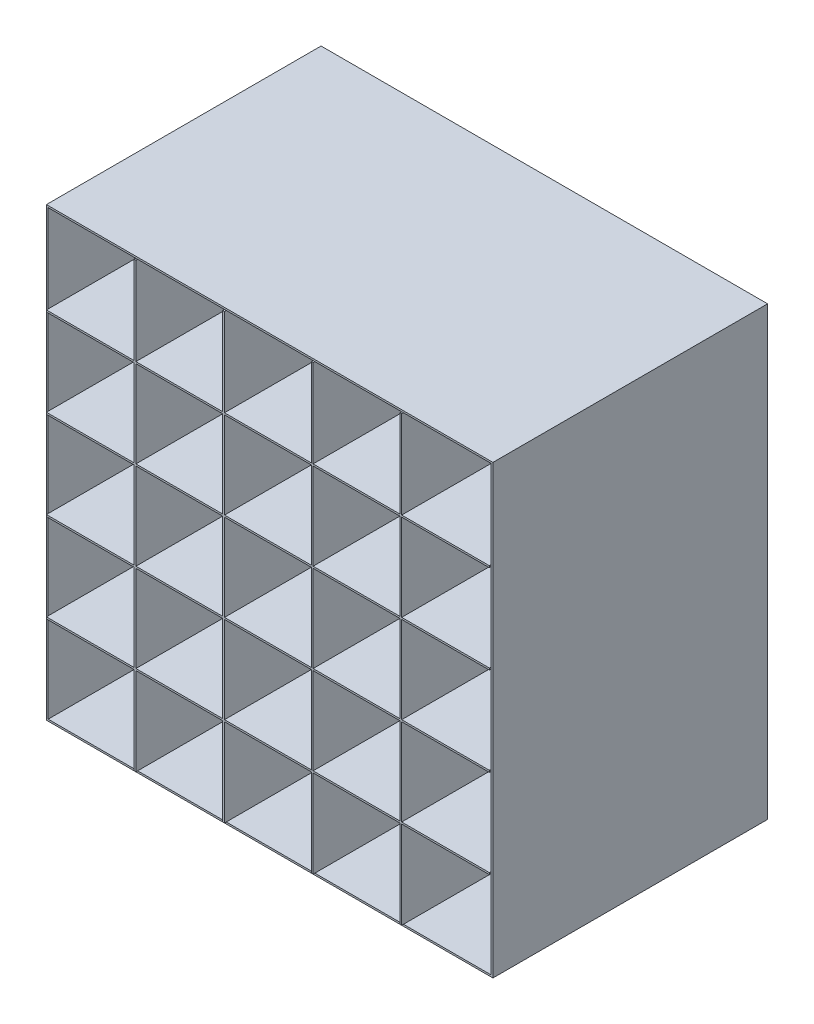
SolidWorks part; units mm, degrees
ref_plane "Alzado" through (0, 0, 0) normal (0, 0, 1) x (1, 0, 0)
ref_plane "Planta" through (0, 0, 0) normal (0, 1, 0) x (1, 0, 0)
ref_plane "Vista lateral" through (0, 0, 0) normal (1, 0, 0) x (0, 0, -1)
sketch "Sketch1" plane through (0, 0, 0) normal (0, 0, 1) x (1, 0, 0)
  line L0 (0, 0) -> (125, 0) construction
  line L1 (125, 0) -> (125, 125) construction
  line L2 (125, 125) -> (-125, 125)
  line L3 (-125, 125) -> (-125, -125)
  line L4 (-125, -125) -> (125, -125)
  line L5 (125, -125) -> (125, 125)
  line L6 (-125, 125) -> (-125, 126) construction
  line L7 (-125, 126) -> (-126, 126)
  line L8 (-126, 126) -> (-126, -126)
  line L9 (-126, -126) -> (126, -126)
  line L10 (-126, 126) -> (126, 126)
  line L11 (126, 126) -> (126, -126)
  dimension "D1" = 125
  dimension "D2" = 125
  dimension "D3" = 250
  dimension "D4" = 250
  dimension "D5" = 1
  dimension "D6" = 1
  dimension "D7" = 252
  dimension "D8" = 252
extrude "Boss-Extrude1" add sketch "Sketch1" along normal blind 50 contours L4 L5 L2 L3 | L10 L11 L9 L8
sketch "Sketch2" plane through (0, 0, 0) normal (0, 0, -1) x (-1, 0, 0)
  line L0 (-126, 126) -> (126, 126)
  line L1 (126, 126) -> (126, -126)
  line L2 (126, -126) -> (-126, -126)
  line L3 (-126, 126) -> (-126, -126) construction
  line L4 (126, -126) -> (-126, -126) construction
  line L5 (-126, -126) -> (-126, 126)
extrude "Boss-Extrude2" add sketch "Sketch2" along normal blind 5 and the other way blind 1
sketch "Sketch3" plane through (0, 0, 1) normal (0, 0, 1) x (1, 0, 0)
  line L0 (-125, 125) -> (-75, 125) construction
  line L1 (125, 125) -> (-125, 125) construction
  line L2 (-75, 125) -> (-25, 125) construction
  line L3 (125, 125) -> (-125, 125) construction
  line L4 (-25, 125) -> (25, 125) construction
  line L5 (25, 125) -> (75, 125) construction
  line L6 (-125, 125) -> (-125, 75) construction
  line L7 (-125, 125) -> (-125, -125) construction
  line L8 (-125, 75) -> (-125, 25) construction
  line L9 (-125, 125) -> (-125, -125) construction
  line L10 (-125, 25) -> (-125, -25) construction
  line L11 (-125, -25) -> (-125, -75) construction
  line L12 (-125, 75) -> (-125, 75.5) construction
  line L13 (-125, 75.5) -> (125, 75.5)
  line L14 (-125, 75.5) -> (-125, 74.5072)
  line L15 (-125, 74.5072) -> (125, 74.5072)
  line L16 (125, 74.5072) -> (125, 75.5)
  line L17 (-125, 25) -> (-125, 25.5)
  line L18 (-125, 25.5) -> (125, 25.5)
  line L19 (125, -125) -> (125, 125) construction
  line L20 (125, 25.5) -> (125, 24.5)
  line L21 (125, 24.5) -> (-125, 24.5)
  line L22 (-125, 24.5) -> (-125, 25.5)
  line L23 (-125, -25) -> (-125, -24.5)
  line L24 (-125, -24.5) -> (125, -24.5)
  line L25 (125, -125) -> (125, 125) construction
  line L26 (125, -24.5) -> (125, -25.5)
  line L27 (125, -25.5) -> (-125, -25.5)
  line L28 (-125, -25.5) -> (-125, -24.5)
  line L29 (-125, -75) -> (-125, -74.5)
  line L30 (-125, -74.5) -> (125, -74.5)
  line L31 (125, -74.5) -> (125, -75.5)
  line L32 (125, -75.5) -> (-125, -75.5)
  line L33 (-125, -75.5) -> (-125, -74.5)
  line L34 (-75, 125) -> (-74.5, 125)
  line L35 (-74.5, 125) -> (-74.5, -125)
  line L36 (-125, -125) -> (125, -125) construction
  line L37 (-74.5, -125) -> (-75.5, -125)
  line L38 (-75.5, -125) -> (-75.5, 125)
  line L39 (-75.5, 125) -> (-74.5, 125)
  line L40 (-25, 125) -> (-24.5, 125)
  line L41 (-24.5, 125) -> (-24.5, -125)
  line L42 (-24.5, -125) -> (-25.5, -125)
  line L43 (-125, -125) -> (125, -125) construction
  line L44 (-25.5, -125) -> (-25.5, 125)
  line L45 (-25.5, 125) -> (-24.5, 125)
  line L46 (25, 125) -> (25.5, 125)
  line L47 (25.5, 125) -> (25.5, -125)
  line L48 (25.5, -125) -> (24.5, -125)
  line L49 (24.5, -125) -> (24.5, 125)
  line L50 (24.5, 125) -> (25.5, 125)
  line L51 (75, 125) -> (75.5, 125)
  line L52 (75.5, 125) -> (75.5, -125)
  line L53 (75.5, -125) -> (74.5, -125)
  line L54 (74.5, -125) -> (74.5, 125)
  line L55 (74.5, 125) -> (75.5, 125)
  dimension "D1" = 50
  dimension "D2" = 50
  dimension "D3" = 50
  dimension "D4" = 50
  dimension "D5" = 50
  dimension "D6" = 50
  dimension "D7" = 50
  dimension "D8" = 50
  dimension "D9" = 49.5
  dimension "D10" = 1
  dimension "D11" = 0.5
  dimension "D12" = 0.5
  dimension "D13" = 1
  dimension "D14" = 0.5
  dimension "D15" = 1
  dimension "D16" = 0.5
  dimension "D17" = 1
  dimension "D18" = 0.5
  dimension "D19" = 1
  dimension "D20" = 0.5
  dimension "D21" = 1
  dimension "D22" = 0.5
  dimension "D23" = 1
extrude "Boss-Extrude3" add sketch "Sketch3" along normal blind 50 contours L30 L31 L32 L33 | L24 L26 L27 L28 | L18 L20 L21 L22 | L15 L16 L13 L14 | L52 L53 L54 L55 | L47 L48 L49 L50 | L41 L42 L44 L45 | L35 L37 L38 L39
sketch "Sketch4" plane through (0, 0, 1) normal (0, 0, 1) x (1, 0, 0)
  line L0 (0, 0) -> (0, 98.6886) construction
  line L1 (0, 98.6886) -> (50, 98.6886) construction
  line L2 (50, 98.6886) -> (100, 98.6886) construction
  line L3 (100, 98.6886) -> (100, 48.6886) construction
  line L4 (100, 48.6886) -> (100, -1.3114) construction
  line L5 (100, -1.3114) -> (100, -51.3114) construction
  line L6 (100, -51.3114) -> (100, -101.3114) construction
  line L7 (100, -101.3114) -> (46.1074, -101.3114) construction
  line L8 (46.1074, -101.3114) -> (0, -101.3114) construction
  line L9 (0, -101.3114) -> (-50, -101.3114) construction
  line L10 (-50, -101.3114) -> (-100, -101.3114) construction
  line L11 (-100, -101.3114) -> (-100, -45.3639) construction
  line L12 (-100, -45.3639) -> (-100, 5.4624) construction
  line L13 (-100, 5.4624) -> (-100, 54.8067) construction
  line L14 (-100, 54.8067) -> (-100, 98.6886) construction
  line L15 (-100, 98.6886) -> (-50, 98.6886) construction
  line L16 (-50, 98.6886) -> (-50, 49.3443) construction
  line L17 (-50, 49.3443) -> (-50, 0) construction
  line L18 (-50, 0) -> (-50, -50.8263) construction
  line L19 (-50, -50.8263) -> (-1.5755, -50.8263) construction
  line L20 (-1.5755, -50.8263) -> (50, -50.8263) construction
  line L21 (50, -50.8263) -> (50, 0) construction
  line L22 (50, 0) -> (50, 49.3443) construction
  line L23 (50, 49.3443) -> (0, 49.3443) construction
  circle A0 centre (-100, 98.6886) radius 2.5
  circle A1 centre (-50, 98.6886) radius 2.5
  circle A2 centre (0, 98.6886) radius 2.5
  circle A3 centre (50, 98.6886) radius 2.5
  circle A4 centre (100, 98.6886) radius 2.5
  circle A5 centre (-50, 48.6886) radius 2.5
  circle A6 centre (0, 48.6886) radius 2.5
  circle A7 centre (50, 48.6886) radius 2.5
  circle A8 centre (100, 48.6886) radius 2.5
  circle A9 centre (-50, -1.3114) radius 2.5
  circle A10 centre (0, -1.3114) radius 2.5
  circle A11 centre (50, -1.3114) radius 2.5
  circle A12 centre (100, -1.3114) radius 2.5
  circle A13 centre (-50, -51.3114) radius 2.5
  circle A14 centre (0, -51.3114) radius 2.5
  circle A15 centre (50, -51.3114) radius 2.5
  circle A16 centre (100, -51.3114) radius 2.5
  circle A17 centre (-50, -101.3114) radius 2.5
  circle A18 centre (0, -101.3114) radius 2.5
  circle A19 centre (50, -101.3114) radius 2.5
  circle A20 centre (100, -101.3114) radius 2.5
  circle A21 centre (-100, 48.6886) radius 2.5
  circle A22 centre (-100, -1.3114) radius 2.5
  circle A23 centre (-100, -51.3114) radius 2.5
  circle A24 centre (-100, -101.3114) radius 2.5
  dimension "D11" = 5
  dimension "D1" = 50
  dimension "D2" = 50
  dimension "D3" = 50
  dimension "D4" = 50
  dimension "D5" = 50
  dimension "D6" = 50
  dimension "D7" = 50
  dimension "D8" = 50
  dimension "D9" = 50
  dimension "D10" = 50
  dimension "D12" = 5
extrude "Cut-Extrude1" cut sketch "Sketch4" against normal through all
sketch "Sketch5" plane through (0, 0, -5) normal (0, 0, -1) x (-1, 0, 0)
  line L0 (-100, 96.1886) -> (-100, 93.6886) construction
  line L1 (-100, 96.1886) -> (126, 96.1886)
  line L2 (126, -126) -> (126, 126) construction
  line L3 (-100, 96.1886) -> (-126, 96.1886)
  line L4 (-126, 126) -> (-126, -126) construction
  line L5 (-126, 96.1886) -> (-126, 93.6886)
  line L6 (-126, 93.6886) -> (126, 93.6886)
  line L7 (126, 93.6886) -> (126, 96.1886)
  line L8 (-100, 46.1886) -> (126, 46.1886)
  line L9 (-100, 46.1886) -> (-126, 46.1886)
  line L10 (-126, 46.1886) -> (-126, 43.6886)
  line L11 (-126, 43.6886) -> (126, 43.6886)
  line L12 (126, 43.6886) -> (126, 46.1886)
  line L13 (-100, -3.8114) -> (126, -3.8114)
  line L14 (-100, -3.8114) -> (-126, -3.8114)
  line L15 (-126, -3.8114) -> (-126, -6.3114)
  line L16 (-126, -6.3114) -> (126, -6.3114)
  line L17 (126, -6.3114) -> (126, -3.8114)
  line L18 (-100, -53.8114) -> (126, -53.8114)
  line L19 (-100, -53.8114) -> (-126, -53.8114)
  line L20 (-126, -53.8114) -> (-126, -56.3114)
  line L21 (-126, -56.3114) -> (126, -56.3114)
  line L22 (126, -56.3114) -> (126, -53.8114)
  line L23 (-100, -103.8114) -> (126, -103.8114)
  line L24 (-100, -103.8114) -> (-126, -103.8114)
  line L25 (-126, -103.8114) -> (-126, -106.3114)
  line L26 (-126, -106.3114) -> (126, -106.3114)
  line L27 (126, -106.3114) -> (126, -103.8114)
  circle A0 centre (-100, 98.6886) radius 2.5 construction
  dimension "D1" = 2.5
  dimension "D2" = 5
extrude "Boss-Extrude4" add sketch "Sketch5" along normal blind 50
sketch "Sketch6" plane through (0, 0, -5) normal (0, 0, -1) x (-1, 0, 0)
  line L0 (126, 126) -> (126, -126)
  line L1 (126, -126) -> (-126, -126)
  line L2 (-126, -126) -> (-126, 126)
  line L3 (-126, 126) -> (126, 126)
  line L4 (126, 126) -> (126, 125) construction
  line L5 (126, 125) -> (125, 125) construction
  line L6 (125, 125) -> (-125, 125)
  line L7 (-125, 125) -> (-125, -125)
  line L10 (125, -125) -> (125, 125)
  line L11 (-125, -125) -> (125, -125)
  dimension "D1" = 1
  dimension "D2" = 1
  dimension "D3" = 250
  dimension "D4" = 250
  dimension "D5" = 250
extrude "Boss-Extrude6" add sketch "Sketch6" along normal blind 100 contours L3 L0 L1 L2 | L10 L6 L7 L11
sketch "Sketch7" plane through (0, 0, -55) normal (0, 0, -1) x (-1, 0, 0)
  line L0 (-125, -6.3114) -> (-125, -3.8114)
  line L1 (-125, -3.8114) -> (125, -3.8114)
  line L2 (125, -3.8114) -> (125, -6.3114)
  line L3 (125, -125) -> (125, 125) construction
  line L4 (-125, -6.3114) -> (125, -6.3114) construction
  line L5 (125, -6.3114) -> (-125, -6.3114)
extrude "Boss-Extrude7" add sketch "Sketch7" along normal blind 50
sketch "Sketch8" plane through (0, -3.8114, 0) normal (0, 1, 0) x (1, 0, 0)
  line L0 (125, 105) -> (100, 105) construction
  line L1 (126, 105) -> (-126, 105) construction
  line L2 (100, 105) -> (50, 105) construction
  line L3 (50, 105) -> (0, 105) construction
  line L4 (0, 105) -> (-50, 105) construction
  line L5 (-50, 105) -> (-100, 105) construction
  line L6 (100, 105) -> (100, 80) construction
  line L7 (50, 105) -> (50, 80) construction
  line L8 (0, 105) -> (0, 80) construction
  line L9 (-50, 105) -> (-50, 80) construction
  line L10 (-100, 105) -> (-100, 80) construction
  line L11 (-100, 85) -> (-50, 85)
  line L12 (-100, 75) -> (-50, 75)
  line L13 (50, 85) -> (100, 85)
  line L14 (50, 75) -> (100, 75)
  arc A0 (100, 75) -> (100, 85) centre (100, 80) ccw
  arc A1 (50, 85) -> (50, 75) centre (50, 80) ccw
  arc A2 (-50, 75) -> (-50, 85) centre (-50, 80) ccw
  arc A3 (-100, 85) -> (-100, 75) centre (-100, 80) ccw
  dimension "D1" = 25
  dimension "D2" = 50
  dimension "D3" = 50
  dimension "D4" = 50
  dimension "D5" = 50
  dimension "D6" = 25
  dimension "D7" = 5
extrude "Cut-Extrude2" cut sketch "Sketch8" against normal blind 50
